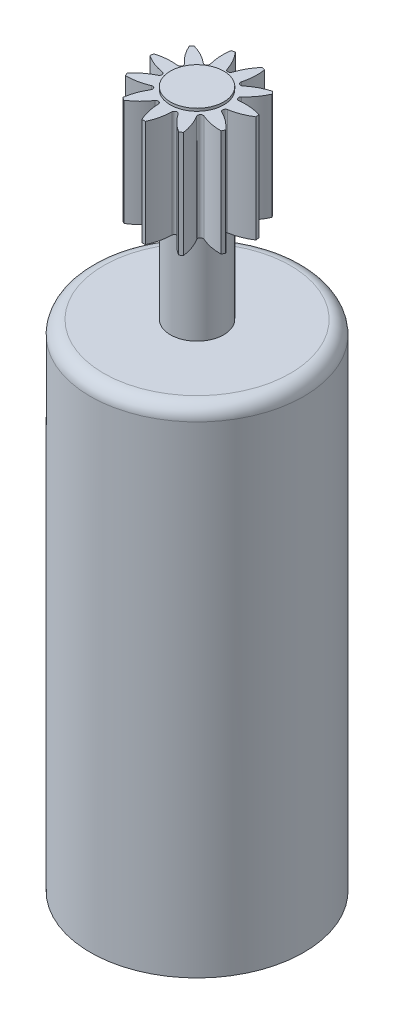
SolidWorks part; units mm, degrees
ref_plane "Ön Düzlem" through (0, 0, 0) normal (0, 0, 1) x (1, 0, 0)
ref_plane "Üst Düzlem" through (0, 0, 0) normal (0, 1, 0) x (1, 0, 0)
ref_plane "Sağ Düzlem" through (0, 0, 0) normal (1, 0, 0) x (0, 0, -1)
sketch "Çizim2" plane through (0, 0, 0) normal (0, 0, 1) x (1, 0, 0)
  line L0 (0, 0) -> (0, 26.1)
  line L1 (0, 26.1) -> (1, 26.1)
  line L2 (1, 26.1) -> (1, 26)
  line L3 (1, 26) -> (2, 26)
  line L4 (2, 26) -> (2, 22)
  line L5 (2, 22) -> (1, 22)
  line L6 (1, 22) -> (1, 18.5414)
  line L7 (1, 18.5414) -> (4, 18.5414)
  line L8 (4, 18.5414) -> (4, 0)
  line L9 (4, 0) -> (0, 0)
  line L10 (0, 0) -> (0, 28.389) construction
  dimension "D1" = 26.1
  dimension "D2" = 1
  dimension "D3" = 0.1
  dimension "D4" = 4
  dimension "D5" = 1
  dimension "D6" = 1
  dimension "D7" = 4
revolve "Döndür1" add sketch "Çizim2" angle 360 about L10
sketch "Çizim4" plane through (0, 26, 0) normal (0, 1, 0) x (1, 0, 0)
  line L0 (0, 0) -> (0, 2) construction
  circle A0 centre (0, 0) radius 2 construction
  arc A1 (-0.5, 1.9365) -> (0.5, 1.9365) centre (0, 0) cw
  arc A2 (0.5, 1.9365) -> (0.0953, 1.2198) centre (2.002, 0.6158) ccw
  arc A3 (0.0953, 1.2198) -> (-0.0953, 1.2198) centre (0, 1.25) cw
  arc A4 (-0.5, 1.9365) -> (-0.0953, 1.2198) centre (-2.002, 0.6158) cw
  dimension "D2" = 2
  dimension "D3" = 0.1
  dimension "D1" = 1
  dimension "D4" = 0.75
extrude "Kes-Ekstrüzyon1" cut sketch "Çizim4" against normal blind 5
pattern_circular "Dairesel Kaplama1" count 11 over 360 about axis through (0, 0, 0) along (0, 1, 0) of "Kes-Ekstrüzyon1"
fillet "Radyus1" radius 0.5 1 edges at (0, 18.5414, -4)
